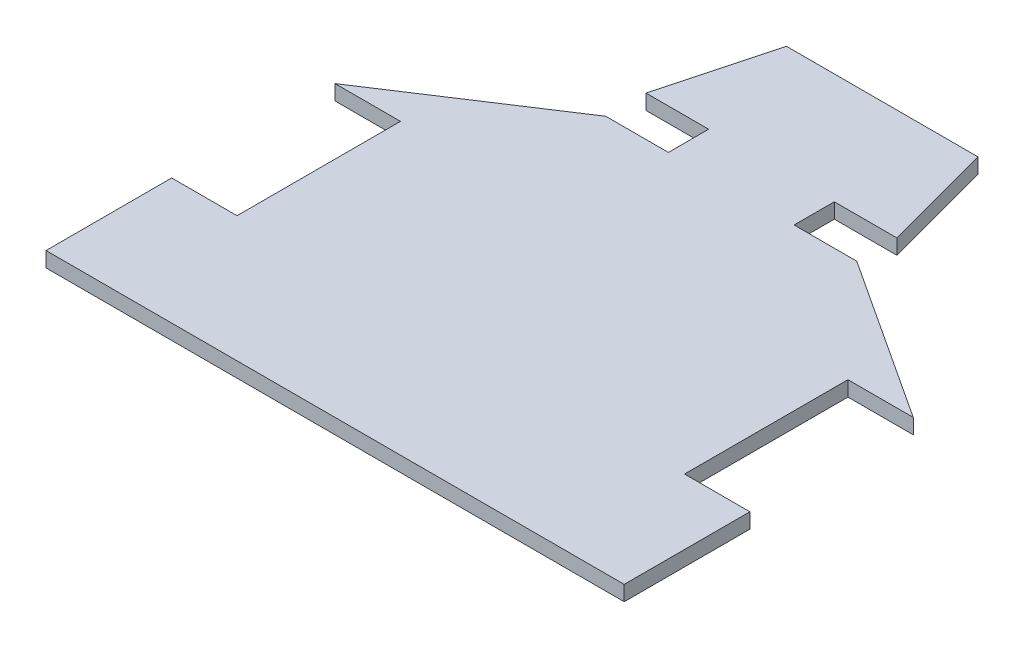
SolidWorks part; units mm, degrees
ref_plane "Front Plane" through (0, 0, 0) normal (0, 0, 1) x (1, 0, 0)
ref_plane "Top Plane" through (0, 0, 0) normal (0, 1, 0) x (1, 0, 0)
ref_plane "Right Plane" through (0, 0, 0) normal (1, 0, 0) x (0, 0, -1)
sketch "Sketch1" plane through (0, 0, 0) normal (0, 1, 0) x (1, 0, 0)
  line L0 (-115, 0) -> (115, 0)
  line L10 (-115, 0) -> (-115, 50)
  line L11 (-115, 50) -> (-89, 50)
  line L12 (-89, 50) -> (-89, 115)
  line L13 (-89, 115) -> (-115, 115)
  line L14 (-115, 115) -> (-49.928, 157.5835)
  line L15 (-49.928, 157.5835) -> (-25, 157.5835)
  line L16 (-25, 157.5835) -> (-25, 173.5835)
  line L17 (-25, 173.5835) -> (-49.928, 173.5835)
  line L18 (-49.928, 173.5835) -> (-38.1086, 217.6315)
  line L19 (-38.1086, 217.6315) -> (38.1086, 217.6315)
  line L20 (115, 0) -> (115, 50)
  line L21 (115, 50) -> (89, 50)
  line L22 (89, 50) -> (89, 115)
  line L23 (89, 115) -> (115, 115)
  line L24 (115, 115) -> (49.928, 157.5835)
  line L28 (49.928, 157.5835) -> (25, 157.5835)
  line L29 (25, 157.5835) -> (25, 173.5835)
  line L30 (25, 173.5835) -> (49.928, 173.5835)
  line L31 (49.928, 173.5835) -> (38.1086, 217.6315)
  line L32 (-25, 157.5835) -> (25, 173.5835) construction
  line L33 (25, 157.5835) -> (-25, 173.5835) construction
  line L34 (-89, 50) -> (89, 115) construction
  line L35 (-89, 115) -> (89, 50) construction
  point P2 (0, 82.5)
  point P4 (0, 0)
  point P9 (0, 217.6315)
  point P10 (0, 165.5835)
  point P27 (-25, 173.5835)
  dimension "D1" = 26
  dimension "D2" = 16
  dimension "D3" = 230
  dimension "D4" = 65
  dimension "D5" = 50
  dimension "D6" = 50
  dimension "D7" = 76.2173
  dimension "D8" = 246.402
  dimension "D9" = 60.0481
  dimension "D10" = 217.6315
extrude "Boss-Extrude1" add sketch "Sketch1" along normal blind 6
